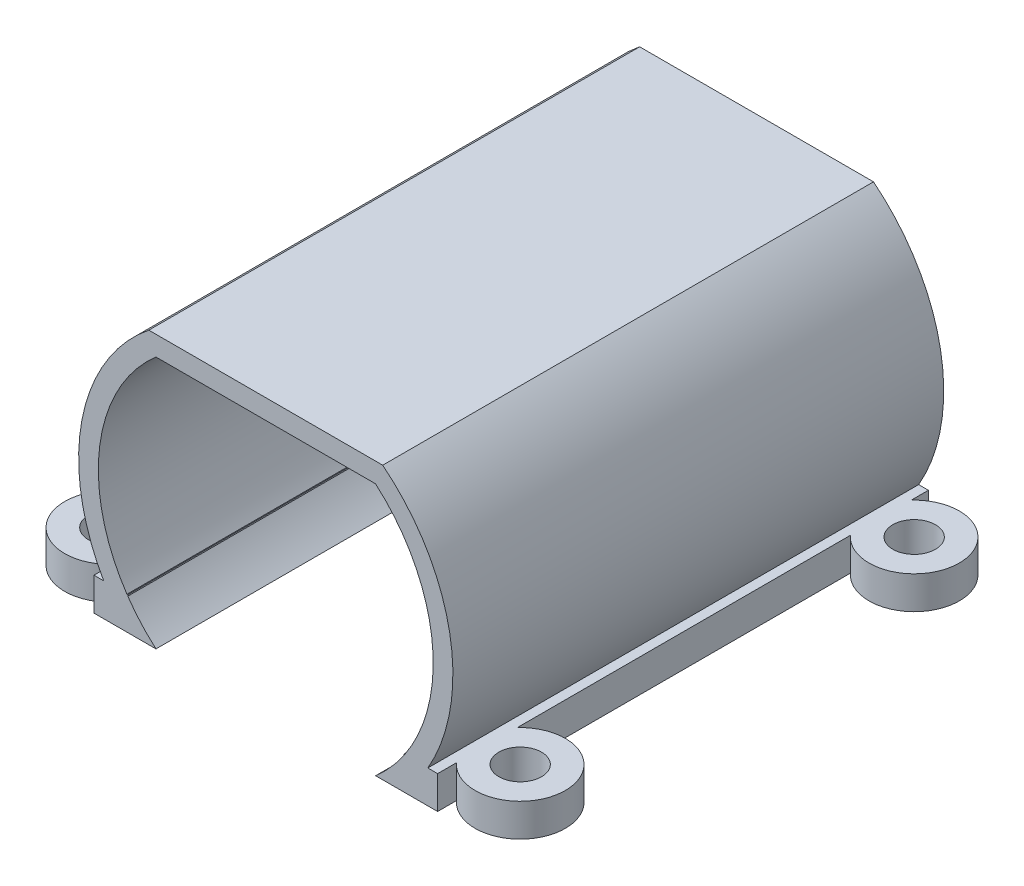
SolidWorks part; units mm, degrees
ref_plane "Alzado" through (0, 0, 0) normal (0, 0, 1) x (1, 0, 0)
ref_plane "Planta" through (0, 0, 0) normal (0, 1, 0) x (1, 0, 0)
ref_plane "Vista lateral" through (0, 0, 0) normal (1, 0, 0) x (0, 0, -1)
sketch "Croquis1" plane through (0, 0, 0) normal (0, 0, 1) x (1, 0, 0)
  line L0 (-6.6895, 7.7) -> (6.6895, 7.7)
  line L1 (-6.6895, -7.7) -> (6.6895, -7.7)
  arc A0 (-6.6895, 7.7) -> (-6.6895, -7.7) centre (0, 0) ccw
  arc A1 (6.6895, -7.7) -> (6.6895, 7.7) centre (0, 0) ccw
  point P5 (0, 0)
  dimension "D1" = 20.4
  dimension "D2" = 7.7
  dimension "D3" = 15.4
extrude "Saliente-Extruir1" add sketch "Croquis1" along normal blind 30
shell "Vaciado1" thickness 1.2
sketch "Croquis2" plane through (0, 0, -1.2) normal (0, 0, -1) x (-1, 0, 0)
  line L1 (-20.823, 15.7006) -> (20.823, 15.7006)
  line L2 (-20.823, 15.7006) -> (-20.823, -15.7006)
  line L3 (-20.823, -15.7006) -> (20.823, -15.7006)
  line L4 (20.823, 15.7006) -> (20.823, -15.7006)
  line L5 (-20.823, 15.7006) -> (20.823, -15.7006) construction
  line L6 (-20.823, -15.7006) -> (20.823, 15.7006) construction
  point P0 (0, 0)
extrude "Cortar-Extruir1" cut sketch "Croquis2" against normal blind 1.3
sketch "Croquis3" plane through (0, 0, 30) normal (0, 0, 1) x (1, 0, 0)
  line L1 (9.3098, -7.7) -> (-9.6926, -7.7)
  line L2 (9.3098, -7.7) -> (9.3098, -10.6722)
  line L3 (9.3098, -10.6722) -> (-9.6926, -10.6722)
  line L4 (-9.6926, -7.7) -> (-9.6926, -10.6722)
extrude "Cortar-Extruir2" cut sketch "Croquis3" against normal blind 48.3
sketch "Croquis4" plane through (0, -7.7, 0) normal (0, -1, 0) x (1, 0, 0)
  line L0 (0, 0) -> (0, 30) construction
  line L1 (6.6895, 30) -> (-6.6895, 30) construction
  line L2 (0, 15) -> (16.7401, 15) construction
  circle A0 centre (12.5, 3) radius 1.3
  circle A1 centre (12.5, 27) radius 1.3
  circle A2 centre (-12.5, 27) radius 1.3
  circle A3 centre (-12.5, 3) radius 1.3
  circle A4 centre (12.5, 3) radius 2.75
  circle A5 centre (12.5, 27) radius 2.75
  circle A6 centre (-12.5, 27) radius 2.75
  circle A7 centre (-12.5, 3) radius 2.75
  dimension "D3" = 2.6
  dimension "D4" = 5.5
  dimension "D1" = 12.5
  dimension "D2" = 12
extrude "Saliente-Extruir2" add sketch "Croquis4" against normal blind 2 separate body
sketch "Croquis5" plane through (0, -7.7, 0) normal (0, -1, 0) x (1, 0, 0)
  line L0 (-7.1239, 30) -> (-11.4, 30) construction
  line L1 (-8.4065, 0.1) -> (-10.4676, 0.1)
  line L2 (-8.4065, 0.1) -> (-8.4065, 30)
  line L3 (-8.4065, 30) -> (-10.4676, 30)
  line L4 (-10.4676, 0.1) -> (-10.4676, 30)
  line L5 (0, 0) -> (0, 12.3583) construction
  line L6 (10.4676, 0.1) -> (10.4676, 30)
  line L7 (8.4065, 30) -> (10.4676, 30)
  line L8 (8.4065, 0.1) -> (8.4065, 30)
  line L9 (8.4065, 0.1) -> (10.4676, 0.1)
extrude "Saliente-Extruir3" add sketch "Croquis5" against normal blind 2
